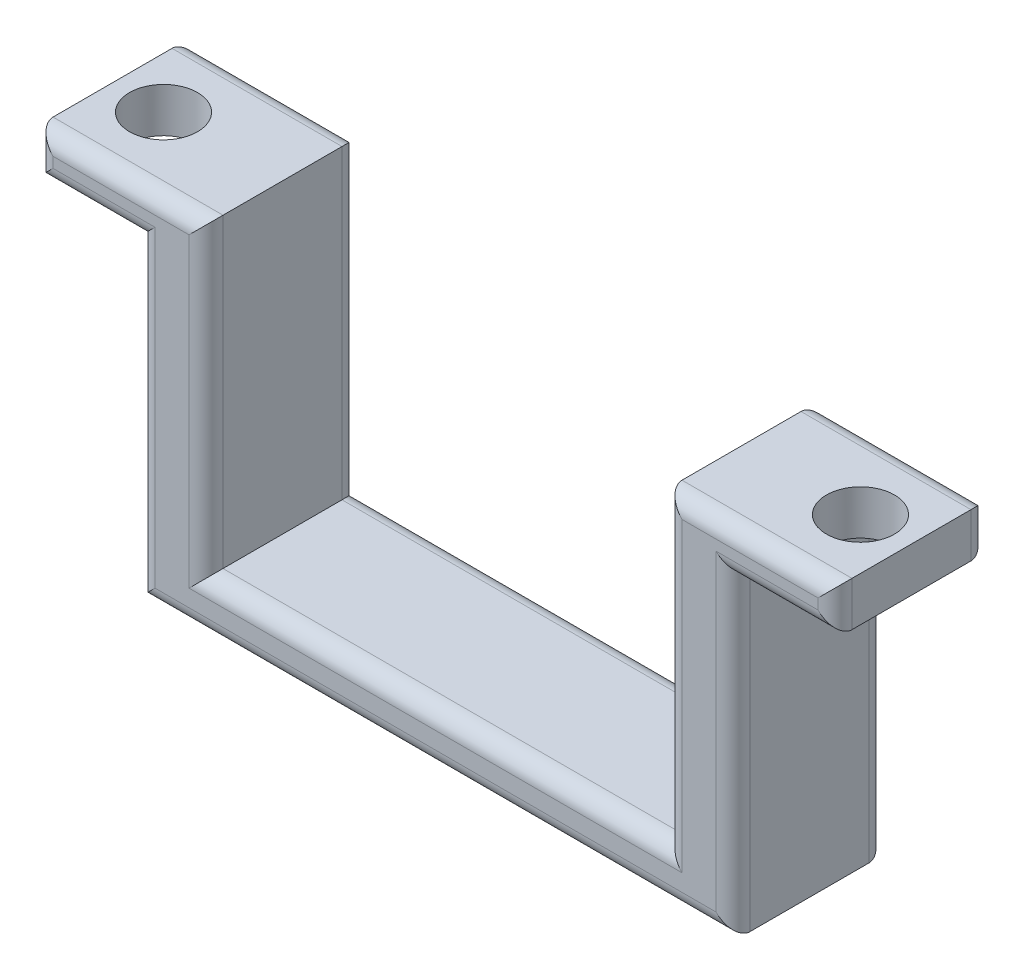
SolidWorks part; units mm, degrees
ref_plane "Front Plane" through (0, 0, 0) normal (0, 0, 1) x (1, 0, 0)
ref_plane "Top Plane" through (0, 0, 0) normal (0, 1, 0) x (1, 0, 0)
ref_plane "Right Plane" through (0, 0, 0) normal (1, 0, 0) x (0, 0, -1)
sketch "Sketch1" plane through (0, 0, 0) normal (0, 0, 1) x (1, 0, 0)
  line L0 (0, 0) -> (10, 0)
  line L1 (10, 0) -> (10, -18)
  line L2 (10, -18) -> (37, -18)
  line L3 (37, -18) -> (37, 0)
  line L4 (37, 0) -> (47, 0)
  line L5 (47, 0) -> (47, -2.6145)
  line L6 (47, -2.6145) -> (41, -2.6145)
  line L7 (41, -2.6145) -> (41, -21)
  line L8 (41, -21) -> (6, -21)
  line L9 (6, -21) -> (6, -2.6145)
  line L10 (6, -2.6145) -> (0, -2.6145)
  line L11 (0, -2.6145) -> (0, 0)
  dimension "D1" = 27
  dimension "D2" = 21
  dimension "D3" = 10
  dimension "D4" = 6
  dimension "D5" = 18
extrude "Boss-Extrude1" add sketch "Sketch1" along normal blind 9
sketch "Sketch2" plane through (0, -2.6145, 0) normal (0, -1, 0) x (1, 0, 0)
  line L0 (3, 9) -> (3, 0) construction
  line L1 (0, 9) -> (6, 9) construction
  line L2 (0, 0) -> (6, 0) construction
  line L3 (0, 4.5) -> (6, 4.5) construction
  line L4 (0, 9) -> (0, 0) construction
  line L5 (6, 9) -> (6, 0) construction
  circle A0 centre (3, 4.5) radius 2
  dimension "D1" = 4
ref_plane "Plane1" through (23.5, 0, 0) normal (1, 0, 0) x (0, 0, -1)
extrude "Cut-Extrude1" cut sketch "Sketch2" against normal blind 9
mirror "Mirror1" about plane through (23.5, 0, 0) normal (1, 0, 0) of "Cut-Extrude1"
fillet "Fillet1" radius 1 24 edges at (3, -2.6145, 0) (6, -11.8072, 0) (23.5, -21, 0) (41, -11.8072, 0) (44, -2.6145, 0) (47, -1.3072, 0) (42, 0, 0) (37, -9, 0) (23.5, -18, 0) (10, -9, 0) (5, 0, 0) (0, -1.3072, 0) (5, 0, 9) (10, -9, 9) (23.5, -18, 9) (37, -9, 9) (42, 0, 9) (47, -1.3072, 9) (44, -2.6145, 9) (41, -11.8072, 9) (23.5, -21, 9) (6, -11.8072, 9) (3, -2.6145, 9) (0, -1.3072, 9)
